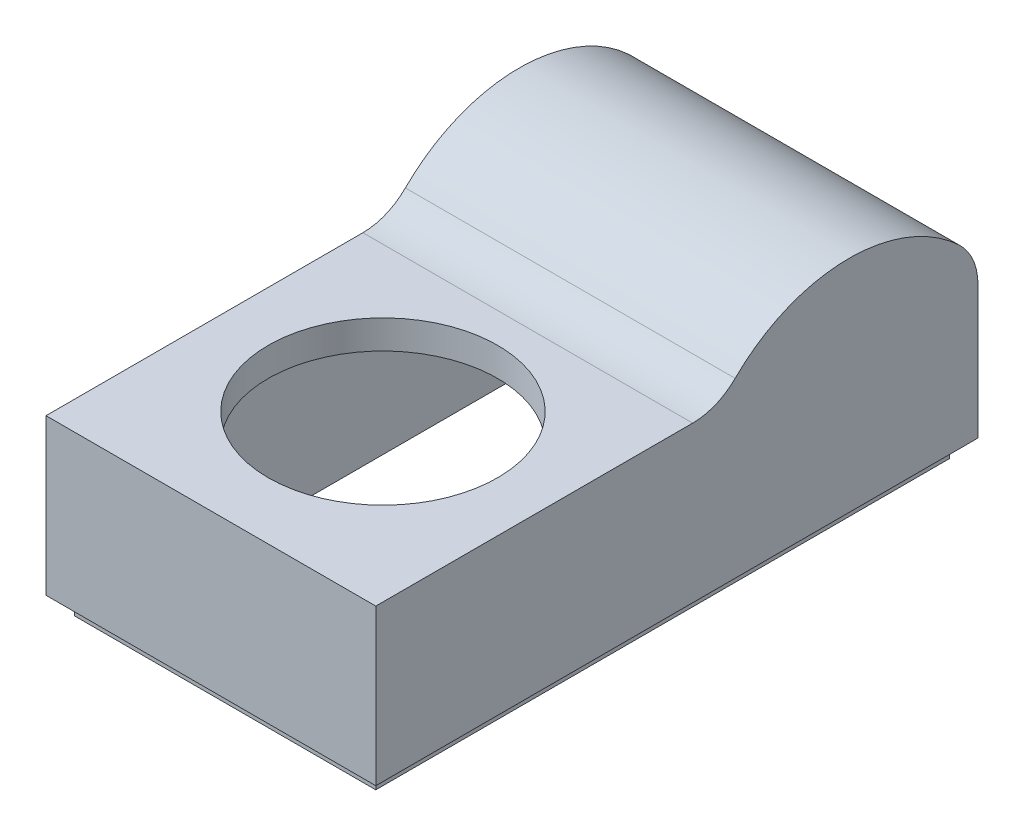
SolidWorks part; units mm, degrees
ref_plane "Front Plane" through (0, 0, 0) normal (0, 0, 1) x (1, 0, 0)
ref_plane "Top Plane" through (0, 0, 0) normal (0, 1, 0) x (1, 0, 0)
ref_plane "Right Plane" through (0, 0, 0) normal (1, 0, 0) x (0, 0, -1)
sketch "Sketch1" plane through (0, 0, 0) normal (0, 1, 0) x (1, 0, 0)
  line L1 (-14.605, 26.67) -> (14.605, 26.67)
  line L2 (-14.605, 26.67) -> (-14.605, -26.67)
  line L3 (-14.605, -26.67) -> (14.605, -26.67)
  line L4 (14.605, 26.67) -> (14.605, -26.67)
  point P4 (0, 26.67)
  point P6 (-14.605, 0)
  dimension "D1" = 53.34
  dimension "D2" = 29.21
extrude "Boss-Extrude1" add sketch "Sketch1" along normal mid plane 19.4945
sketch "Sketch2" plane through (14.605, 0, 0) normal (1, 0, 0) x (0, 0, -1)
  line L0 (-26.67, 4.0323) -> (3.81, 4.0323)
  line L1 (-26.67, 9.7472) -> (-26.67, -9.7472) construction
  line L2 (26.67, 9.7472) -> (26.67, -9.7472) construction
  line L8 (26.67, 4.0323) -> (26.67, 9.7472)
  line L9 (26.67, 9.7472) -> (-26.67, 9.7472)
  line L10 (-26.67, 9.7472) -> (-26.67, 4.0323)
  arc A0 (3.81, 4.0323) -> (26.67, 4.0323) centre (15.24, -4.5403) cw
  point P9 (15.24, 9.7473)
  line M3 (26.67, -9.7472) -> (26.67, 9.7472)
  line M4 (26.67, 9.7472) -> (-26.67, 9.7472)
  line M5 (-26.67, 9.7472) -> (-26.67, -9.7472)
  dimension "D1" = 5.715
  dimension "D3" = 22.86
extrude "Cut-Extrude1" cut sketch "Sketch2" against normal up to surface (29.21 mm away) contours L0 A0 L9 M5 | A0 M4 M3 up to face at (-14.605, 0, 0)
fillet "Fillet1" radius 5.334 1 edges at (0, 4.0323, -3.81)
fillet "Fillet2" radius 5.334 1 edges at (0, 4.0323, -26.67)
shell "Shell1" thickness 2.54
sketch "Sketch3" plane through (0, 4.0323, 0) normal (0, 1, 0) x (1, 0, 0)
  line L0 (-14.605, -11.43) -> (14.605, -11.43) construction
  line L1 (-14.605, 1.3976) -> (-14.605, -26.67) construction
  line L2 (14.605, -26.67) -> (14.605, 1.3976) construction
  line L4 (0, -1.27) -> (0, -21.59) construction
  line L5 (-14.605, -26.67) -> (14.605, -26.67) construction
  circle A0 centre (0, -11.43) radius 10.16
  point P9 (0, -11.43)
  dimension "D2" = 20.32
  dimension "D1" = 5.08
extrude "Cut-Extrude2" cut sketch "Sketch3" against normal blind 24.13
sketch "Sketch5" plane through (0, 0, -26.67) normal (0, 0, -1) x (-1, 0, 0)
  line L0 (-14.605, -9.7472) -> (14.605, -9.7472) construction
  line L1 (-5.3975, -9.7472) -> (5.3975, -9.7472)
  line L2 (-5.3975, -9.7472) -> (-5.3975, -8.1597)
  line L3 (-5.3975, -8.1597) -> (5.3975, -8.1597)
  line L4 (5.3975, -9.7472) -> (5.3975, -8.1597)
  point P6 (0, -8.1597)
  dimension "D1" = 1.5875
  dimension "D2" = 10.795
extrude "Cut-Extrude3" cut sketch "Sketch5" against normal up to surface (2.54 mm away) up to face at (0, -3.8649, -24.13)
sketch "Sketch4" plane through (0, -9.7472, 0) normal (0, -1, 0) x (1, 0, 0)
  line L0 (-5.3975, -24.13) -> (-12.065, -24.13) construction
  line L1 (12.065, -24.13) -> (5.3975, -24.13) construction
  line L2 (12.065, 24.13) -> (12.065, -24.13) construction
  line L3 (-12.065, 24.13) -> (12.065, 24.13) construction
  line L4 (-12.065, -24.13) -> (-12.065, 24.13) construction
  line L5 (-5.3975, -24.13) -> (-12.065, -24.13)
  line L6 (12.065, -24.13) -> (5.3975, -24.13)
  line L7 (12.065, 24.13) -> (12.065, -24.13)
  line L8 (-12.065, 24.13) -> (12.065, 24.13)
  line L9 (-12.065, -24.13) -> (-12.065, 24.13)
  line L10 (-5.3975, -25.4) -> (-5.3975, -24.13)
  line L11 (5.3975, -25.4) -> (5.3975, -24.13)
  line L56 (-13.335, 25.4) -> (-13.335, -25.4)
  line L57 (-13.335, -25.4) -> (-5.3975, -25.4)
  line L58 (-5.3975, -25.4) -> (5.3975, -25.4)
  line L59 (5.3975, -25.4) -> (13.335, -25.4)
  line L60 (13.335, -25.4) -> (13.335, 25.4)
  line L61 (13.335, 25.4) -> (-13.335, 25.4)
  line L62 (-13.335, 25.4) -> (-13.335, -25.4)
  line L63 (-13.335, -25.4) -> (-5.3975, -25.4)
  line L65 (5.3975, -25.4) -> (13.335, -25.4)
  line L66 (13.335, -25.4) -> (13.335, 25.4)
  line L67 (13.335, 25.4) -> (-13.335, 25.4)
  dimension "D1" = 1.27
extrude "Boss-Extrude2" add sketch "Sketch4" along normal blind 1.5875
